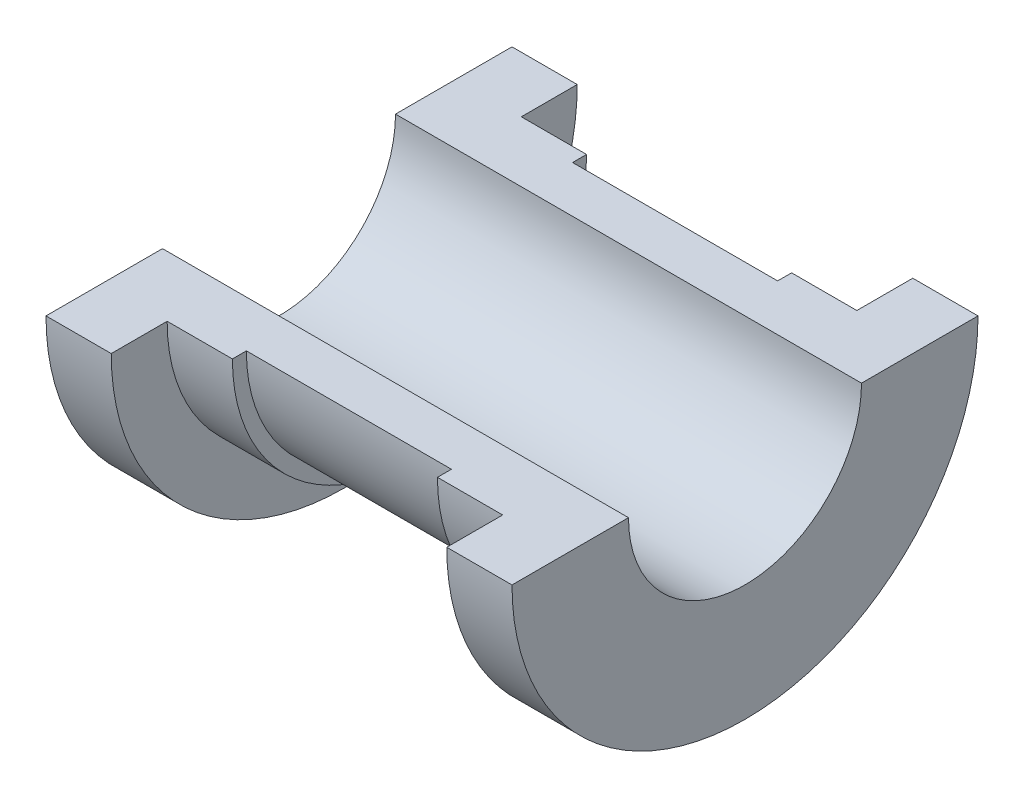
SolidWorks part; units mm, degrees
ref_plane "Front Plane" through (0, 0, 0) normal (0, 0, 1) x (1, 0, 0)
ref_plane "Top Plane" through (0, 0, 0) normal (0, 1, 0) x (1, 0, 0)
ref_plane "Right Plane" through (0, 0, 0) normal (1, 0, 0) x (0, 0, -1)
sketch "Sketch1" plane through (0, 0, 0) normal (0, 0, 1) x (1, 0, 0)
  line L0 (-25, 0) -> (25, 0)
  line L1 (25, 0) -> (25, 25)
  line L2 (25, 25) -> (18, 25)
  line L3 (18, 25) -> (18, 19)
  line L4 (18, 19) -> (11, 19)
  line L5 (11, 19) -> (11, 17.5)
  line L6 (11, 17.5) -> (-11, 17.5)
  line L8 (-11, 19) -> (-11, 17.5)
  line L9 (-18, 19) -> (-11, 19)
  line L10 (-18, 25) -> (-18, 19)
  line L11 (-25, 25) -> (-18, 25)
  line L12 (-25, 0) -> (-25, 25)
  dimension "D2" = 25
  dimension "D4" = 7
  dimension "D5" = 7
  dimension "D7" = 1.5
  dimension "D8" = 6
revolve "Revolve1" add sketch "Sketch1" angle 360 about L0
sketch "Sketch2" plane through (-25, 0, 0) normal (-1, 0, 0) x (0, 0, 1)
  circle A0 centre (0, 0) radius 12.5
extrude "Cut-Extrude1" cut sketch "Sketch2" against normal through all contours A0
sketch "Sketch3" plane through (-25, 0, 0) normal (-1, 0, 0) x (0, 0, 1)
  line L0 (-25, 0) -> (25, 0)
  circle A0 centre (0, 0) radius 25 construction
extrude "Cut-Extrude4" cut sketch "Sketch3" against normal through all and the other way through all
ref_plane "Plane2" through (0, -17.5, 0) normal (0, 1, 0) x (1, 0, 0)
sketch "Sketch5" plane through (0, -17.5, 0) normal (0, 1, 0) x (1, 0, 0)
  circle A0 centre (0, 0) radius 3
extrude "Boss-Extrude1" add sketch "Sketch5" against normal blind 5 separate body
